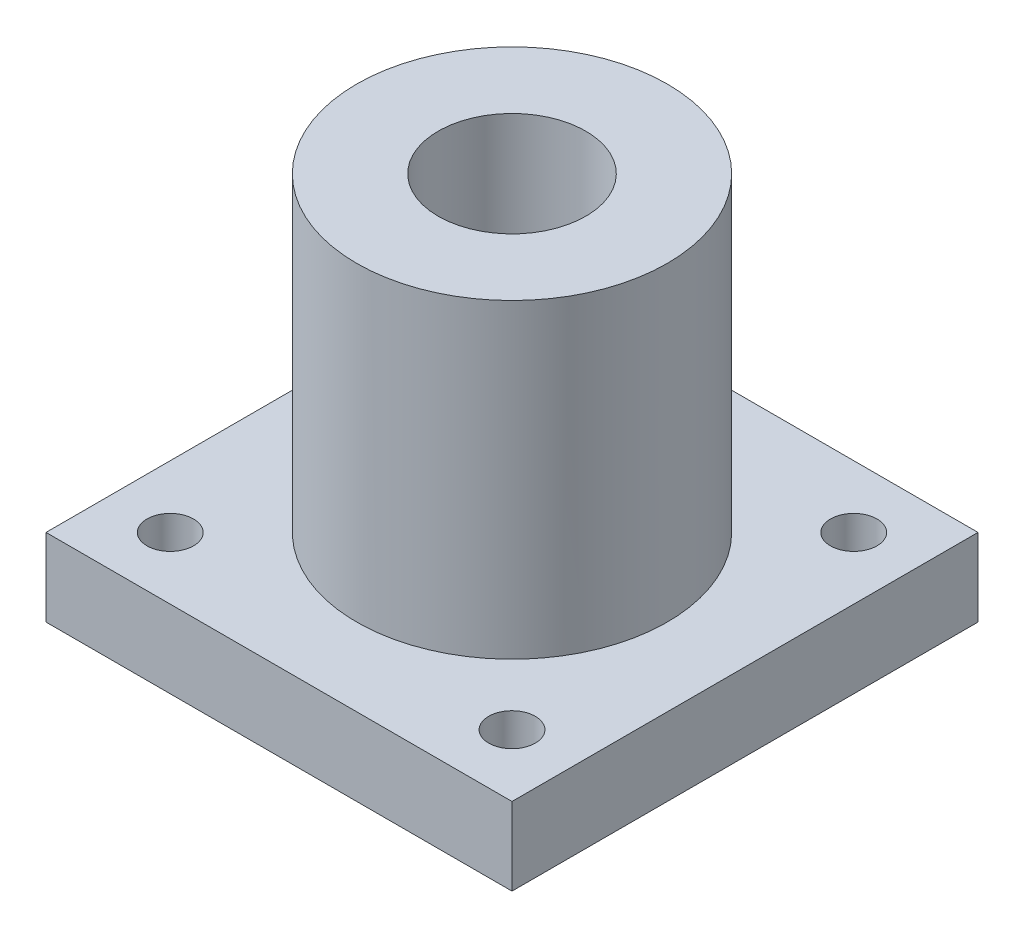
SolidWorks part; units mm, degrees
ref_plane "Ön Düzlem" through (0, 0, 0) normal (0, 0, 1) x (1, 0, 0)
ref_plane "Üst Düzlem" through (0, 0, 0) normal (0, 1, 0) x (1, 0, 0)
ref_plane "Sağ Düzlem" through (0, 0, 0) normal (1, 0, 0) x (0, 0, -1)
sketch "Çizim1" plane through (0, 0, 0) normal (0, 1, 0) x (1, 0, 0)
  line L1 (0, 0) -> (30, 0)
  line L2 (0, 0) -> (0, 30)
  line L3 (0, 30) -> (30, 30)
  line L4 (30, 0) -> (30, 30)
  circle A0 centre (15, 15) radius 4.75
  dimension "D1" = 9.5
  dimension "D2" = 30
  dimension "D3" = 30
  dimension "D4" = 15
  dimension "D5" = 15
extrude "Yükseklik-Ekstrüzyon1" add sketch "Çizim1" along normal blind 5
sketch "Çizim2" plane through (0, 5, 0) normal (0, 1, 0) x (1, 0, 0)
  circle A0 centre (15, 15) radius 10
  circle A1 centre (15, 15) radius 4.75
  dimension "D1" = 20
  dimension "D2" = 9.5
extrude "Yükseklik-Ekstrüzyon2" add sketch "Çizim2" along normal blind 20
sketch "Çizim3" plane through (0, 5, 0) normal (0, 1, 0) x (1, 0, 0)
  line L0 (0, 0) -> (30, 0) construction
  line L1 (30, 0) -> (30, 30) construction
  line L2 (30, 30) -> (0, 30) construction
  circle A0 centre (4, 26) radius 1.5
  circle A1 centre (26, 26) radius 1.5
  circle A2 centre (26, 4) radius 1.5
  circle A3 centre (4, 4) radius 1.5
  dimension "D1" = 3
  dimension "D2" = 4
  dimension "D3" = 4
  dimension "D4" = 4
  dimension "D5" = 4
extrude "Kes-Ekstrüzyon1" cut sketch "Çizim3" against normal blind 7
